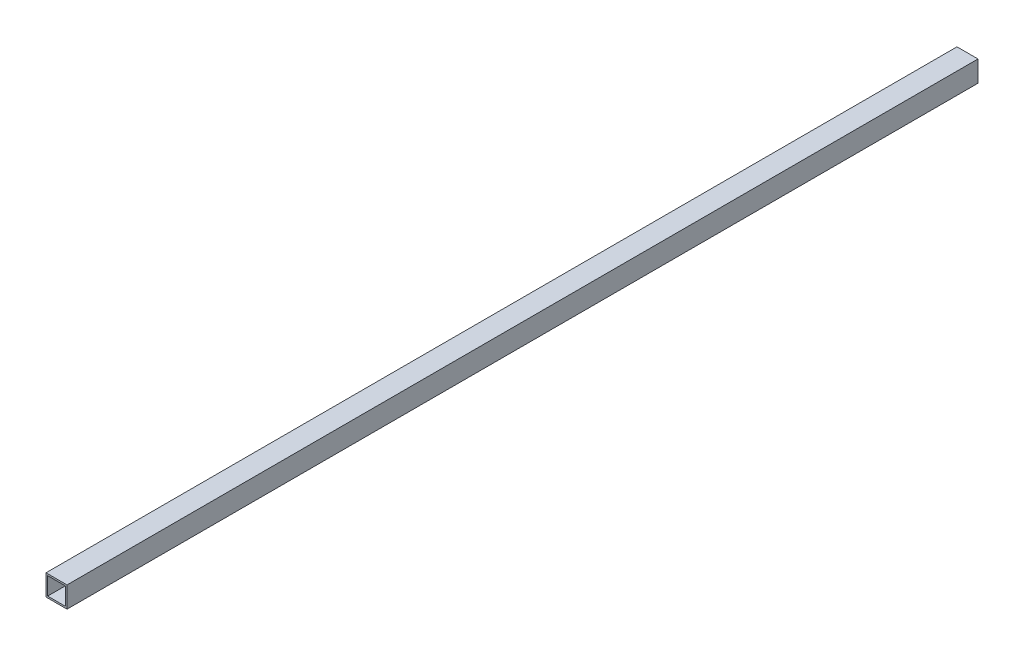
SolidWorks part; units mm, degrees
material "7050-T73510"
ref_plane "Front" through (0, 0, 0) normal (0, 0, 1) x (1, 0, 0)
ref_plane "Top" through (0, 0, 0) normal (0, 1, 0) x (1, 0, 0)
ref_plane "Right" through (0, 0, 0) normal (1, 0, 0) x (0, 0, -1)
sketch "草图1" plane through (0, 0, 0) normal (0, 0, 1) x (1, 0, 0)
  line L0 (-6.3, -6.3) -> (-6.3, 6.3)
  line L1 (-7.5, -7.5) -> (7.5, -7.5)
  line L2 (-7.5, -7.5) -> (-7.5, 7.5)
  line L3 (-7.5, 7.5) -> (7.5, 7.5)
  line L4 (7.5, -7.5) -> (7.5, 7.5)
  line L5 (-7.5, -7.5) -> (7.5, 7.5) construction
  line L6 (-7.5, 7.5) -> (7.5, -7.5) construction
  line L7 (-6.3, 6.3) -> (6.3, 6.3)
  line L8 (6.3, -6.3) -> (6.3, 6.3)
  line L9 (-6.3, -6.3) -> (6.3, -6.3)
  point P0 (0, 0)
  dimension "D1" = 15
  dimension "D2" = 15
  dimension "D3" = 1.2
extrude "凸台-拉伸1" add sketch "草图1" along normal blind 650
